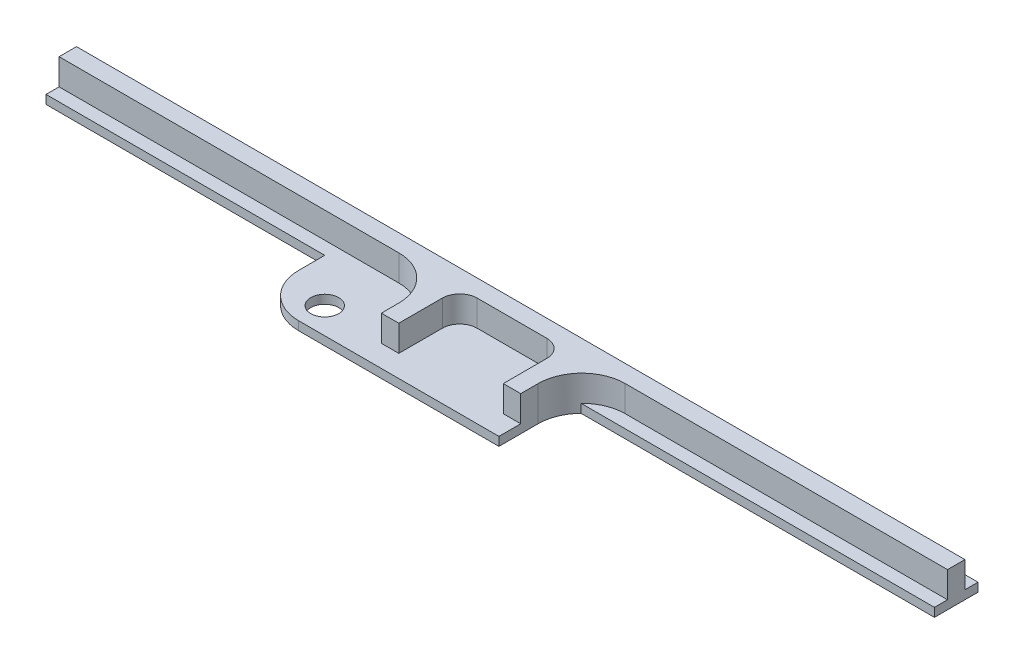
SolidWorks part; units mm, degrees
ref_plane "前视基准面" through (0, 0, 0) normal (0, 0, 1) x (1, 0, 0)
ref_plane "上视基准面" through (0, 0, 0) normal (0, 1, 0) x (1, 0, 0)
ref_plane "右视基准面" through (0, 0, 0) normal (1, 0, 0) x (0, 0, -1)
other "Configuration Table"
sketch "草图1" plane through (0, 0, 0) normal (0, 1, 0) x (1, 0, 0)
  line L0 (-37, 10) -> (-37, 5)
  line L1 (-37, 5) -> (-5, 5)
  line L2 (-5, 5) -> (-5, -3)
  line L3 (-5, -3) -> (35, -3)
  line L4 (35, -3) -> (35, 5)
  line L5 (35, 5) -> (65, 5)
  line L6 (65, 5) -> (65, 10)
  line L7 (65, 10) -> (-37, 10)
  circle A0 centre (0, 0) radius 1.6
  circle A1 centre (30, 0) radius 1.6
  point P7 (-5, -4.1016)
  dimension "D1" = 30
  dimension "D2" = 3.2
  dimension "D3" = 3
  dimension "D5" = 5
  dimension "D4" = 5
  dimension "D6" = 5
  dimension "D7" = 5
  dimension "D8" = 32
  dimension "D9" = 30
extrude "凸台-拉伸1" add sketch "草图1" along normal blind 1
sketch "草图2" plane through (0, 1, 0) normal (0, 1, 0) x (1, 0, 0)
  line L0 (-37, 10) -> (-37, 5) construction
  line L1 (-37, 8.5) -> (65, 8.5)
  line L2 (-37, 8.5) -> (-37, 6.5)
  line L3 (-37, 6.5) -> (65, 6.5)
  line L4 (65, 8.5) -> (65, 6.5)
  line L5 (65, 5) -> (65, 10) construction
  line L6 (-37, 7.5) -> (65, 7.5) construction
  dimension "D1" = 2
extrude "凸台-拉伸2" add sketch "草图2" along normal blind 3
sketch "草图3" plane through (0, 1, 0) normal (0, 1, 0) x (1, 0, 0)
  line L0 (-37, 6.5) -> (65, 6.5) construction
  line L1 (7, 6.5) -> (9, 6.5)
  line L2 (7, 6.5) -> (7, -0.5)
  line L3 (7, -0.5) -> (9, -0.5)
  line L4 (9, 6.5) -> (9, -0.5)
  line L7 (23, 6.5) -> (21, 6.5)
  line L8 (23, 6.5) -> (23, -0.5)
  line L9 (23, -0.5) -> (21, -0.5)
  line L10 (21, 6.5) -> (21, -0.5)
  circle A0 centre (0, 0) radius 1.6 construction
  circle A1 centre (30, 0) radius 1.6 construction
  point P16 (0, 0)
  point P17 (0, 0)
  point P18 (0, 0)
  point P19 (0, 0)
  dimension "D1" = 7
  dimension "D2" = 2
  dimension "D3" = 2
  dimension "D4" = 7
  dimension "D5" = 7
extrude "凸台-拉伸3" add sketch "草图3" along normal blind 3
fillet "圆角1" radius 5 4 edges at (23, 2.5, -6.5) (7, 2.5, -6.5) (35, 0.5, 3) (-5, 0.5, 3)
fillet "圆角2" radius 2 2 edges at (21, 2.5, -6.5) (9, 2.5, -6.5)
sketch "草图4" plane through (0, 1, 0) normal (0, 1, 0) x (1, 0, 0)
  line L0 (0, -3) -> (30, -3) construction
  line L1 (35, 2) -> (35, 5) construction
  line L2 (23, -0.5) -> (23, 1.5) construction
  line L3 (23, -3) -> (30, -3)
  line L4 (35, 2) -> (35, 5)
  line L5 (23, -0.5) -> (23, 1.5)
  line L6 (23, -0.5) -> (23, -3)
  line L10 (35, 5) -> (24.4293, 5)
  arc A0 (30, -3) -> (35, 2) centre (30, 2) ccw construction
  arc A1 (28, 6.5) -> (23, 1.5) centre (28, 1.5) ccw construction
  arc A2 (30, -3) -> (35, 2) centre (30, 2) ccw
  arc A3 (24.4293, 5) -> (23, 1.5) centre (28, 1.5) ccw
extrude "切除-拉伸1" cut sketch "草图4" against normal up to next
